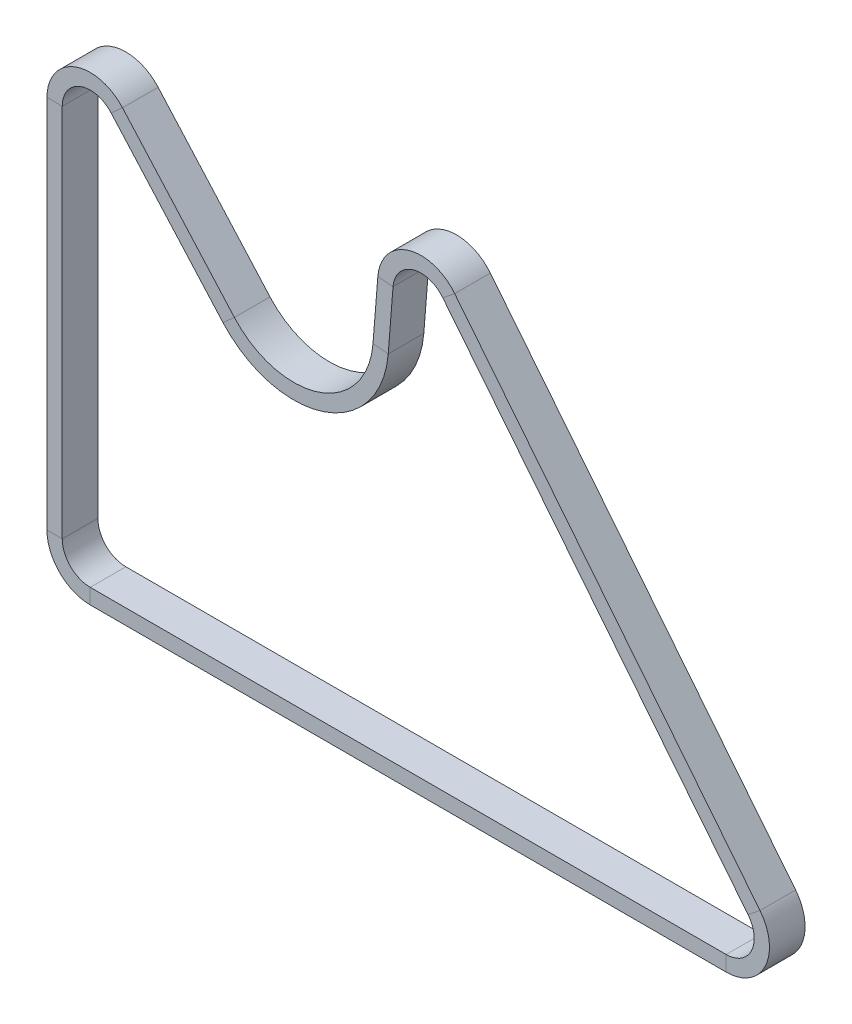
SolidWorks part; units mm, degrees
ref_plane "Front Plane" through (0, 0, 0) normal (0, 0, 1) x (1, 0, 0)
ref_plane "Top Plane" through (0, 0, 0) normal (0, 1, 0) x (1, 0, 0)
ref_plane "Right Plane" through (0, 0, 0) normal (1, 0, 0) x (0, 0, -1)
sketch "Sketch2" plane through (0, 0, 0) normal (0, 0, 1) x (1, 0, 0)
  line L0 (0, 0) -> (1, 0) construction
  line L1 (0, 0) -> (0, 1) construction
  line L2 (64.1414, 7.2746) -> (66.0444, 31.114)
  line L3 (90.9322, 38.7457) -> (210.9322, -111.2543)
  line L4 (200, -134) -> (-50, -134)
  line L5 (-64, -120) -> (-64, 27.2824)
  line L6 (-39.5449, 36.5931) -> (4.4222, -12.7781)
  arc A0 (4.4222, -12.7781) -> (64.1414, 7.2746) centre (30, 10) ccw
  arc A1 (66.0444, 31.114) -> (90.9322, 38.7457) centre (80, 30) cw
  arc A2 (210.9322, -111.2543) -> (200, -134) centre (200, -120) cw
  arc A3 (-50, -134) -> (-64, -120) centre (-50, -120) cw
  arc A4 (-64, 27.2824) -> (-39.5449, 36.5931) centre (-50, 27.2824) cw
ref_plane "Plane1" through (-50, -134, 0) normal (-1, 0, 0) x (0, 0, 1)
sketch "Sketch3" plane through (-50, -134, 0) normal (-1, 0, 0) x (0, 0, 1)
  line L1 (-7, 3) -> (7, 3)
  line L2 (-7, 3) -> (-7, -3)
  line L3 (-7, -3) -> (7, -3)
  line L4 (7, 3) -> (7, -3)
  line L5 (-7, 3) -> (7, -3) construction
  line L6 (-7, -3) -> (7, 3) construction
  line L7 (0, 0) -> (0, 14) construction
  point P0 (0, 0)
  dimension "D1" = 14
  dimension "D2" = 0
  dimension "D3" = 6
  dimension "D4" = 14
sweep "Sweep1" add profiles "Sketch3" path "Sketch2"
